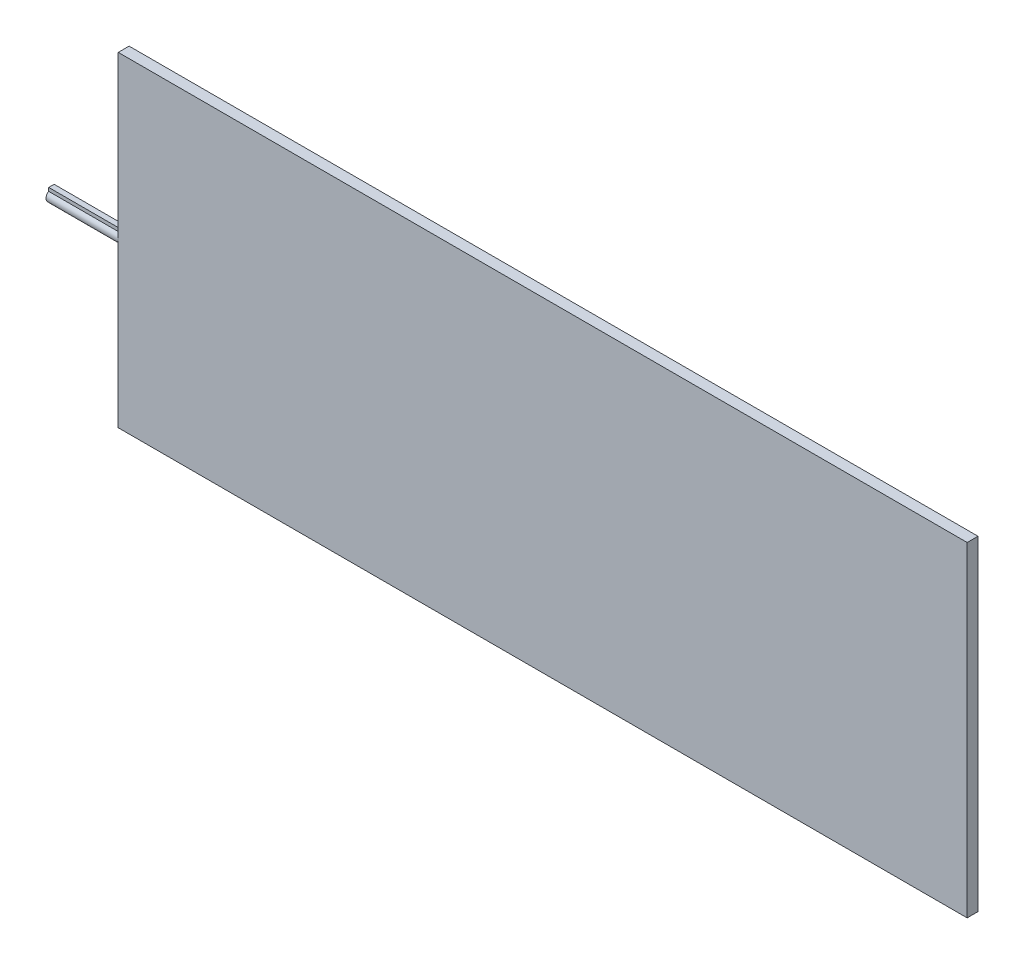
SolidWorks part; units mm, degrees
ref_plane "前视基准面" through (0, 0, 0) normal (0, 0, 1) x (1, 0, 0)
ref_plane "上视基准面" through (0, 0, 0) normal (0, 1, 0) x (1, 0, 0)
ref_plane "右视基准面" through (0, 0, 0) normal (1, 0, 0) x (0, 0, -1)
sketch "草图1" plane through (0, 0, 0) normal (0, 0, 1) x (1, 0, 0)
  line L1 (-117.5, -45) -> (117.5, -45)
  line L2 (-117.5, -45) -> (-117.5, 45)
  line L3 (-117.5, 45) -> (117.5, 45)
  line L4 (117.5, -45) -> (117.5, 45)
  line L5 (-117.5, -45) -> (117.5, 45) construction
  line L6 (-117.5, 45) -> (117.5, -45) construction
  point P0 (0, 0)
  dimension "D1" = 235
  dimension "D2" = 90
extrude "凸台-拉伸1" add sketch "草图1" along normal blind 3
sketch "草图2" plane through (-117.5, 0, 0) normal (-1, 0, 0) x (0, 0, 1)
  line L0 (0, 0) -> (3, 0) construction
  line L1 (3, 45) -> (3, -45) construction
  line L3 (0.75, 2.25) -> (2.25, 2.25)
  line L4 (0.75, 2.25) -> (0.75, 1.299)
  line L6 (2.25, 2.25) -> (2.25, 1.299)
  line L7 (0.75, 2.25) -> (2.25, 0.75) construction
  line L8 (0.75, 0.75) -> (2.25, 2.25) construction
  arc A0 (0.75, 1.299) -> (2.25, 1.299) centre (1.5, 0) ccw
  point P7 (1.5, 1.5)
  dimension "D1" = 3
  dimension "D2" = 1.5
  dimension "D3" = 1.5
extrude "凸台-拉伸2" add sketch "草图2" along normal blind 20
